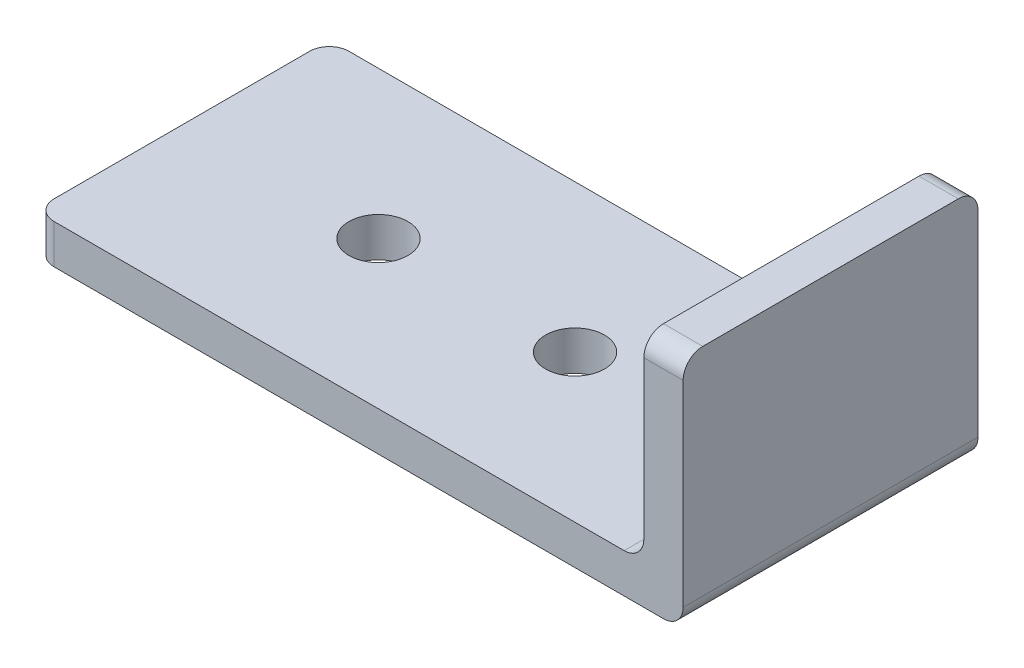
SolidWorks part; units mm, degrees
ref_plane "Front Plane" through (0, 0, 0) normal (0, 0, 1) x (1, 0, 0)
ref_plane "Top Plane" through (0, 0, 0) normal (0, 1, 0) x (1, 0, 0)
ref_plane "Right Plane" through (0, 0, 0) normal (1, 0, 0) x (0, 0, -1)
sketch "Sketch1" plane through (0, 0, 0) normal (0, 1, 0) x (1, 0, 0)
  line L0 (0, 7.5) -> (33, 7.5)
  line L1 (0, 0) -> (33, 0)
  line L2 (0, 0) -> (0, 15)
  line L3 (0, 15) -> (33, 15)
  line L4 (33, 0) -> (33, 15)
  circle A0 centre (10, 7.5) radius 1.5
  circle A1 centre (20, 7.5) radius 1.5
  dimension "D3" = 10
  dimension "D4" = 10
  dimension "D5" = 7.5
  dimension "D1" = 15
  dimension "D2" = 33
extrude "Boss-Extrude1" add sketch "Sketch1" along normal blind 2 contours A1 L0 A0 L2 L1 L4 | A1 L0 L4 L3 L2 A0
sketch "Sketch2" plane through (0, 2, 0) normal (0, 1, 0) x (1, 0, 0)
  line L0 (0, 0) -> (33, 0) construction
  line L1 (33, 15) -> (31, 15)
  line L2 (33, 15) -> (33, 0)
  line L3 (33, 0) -> (31, 0)
  line L4 (31, 15) -> (31, 0)
  dimension "D1" = 2
extrude "Boss-Extrude2" add sketch "Sketch2" along normal blind 10
fillet "Fillet1" radius 1 5 edges at (31, 2, -7.5) (32, 12, 0) (32, 12, -15) (0, 1, 0) (0, 1, -15)
fillet "Fillet2" radius 1 1 edges at (33, 0, -7.5)
